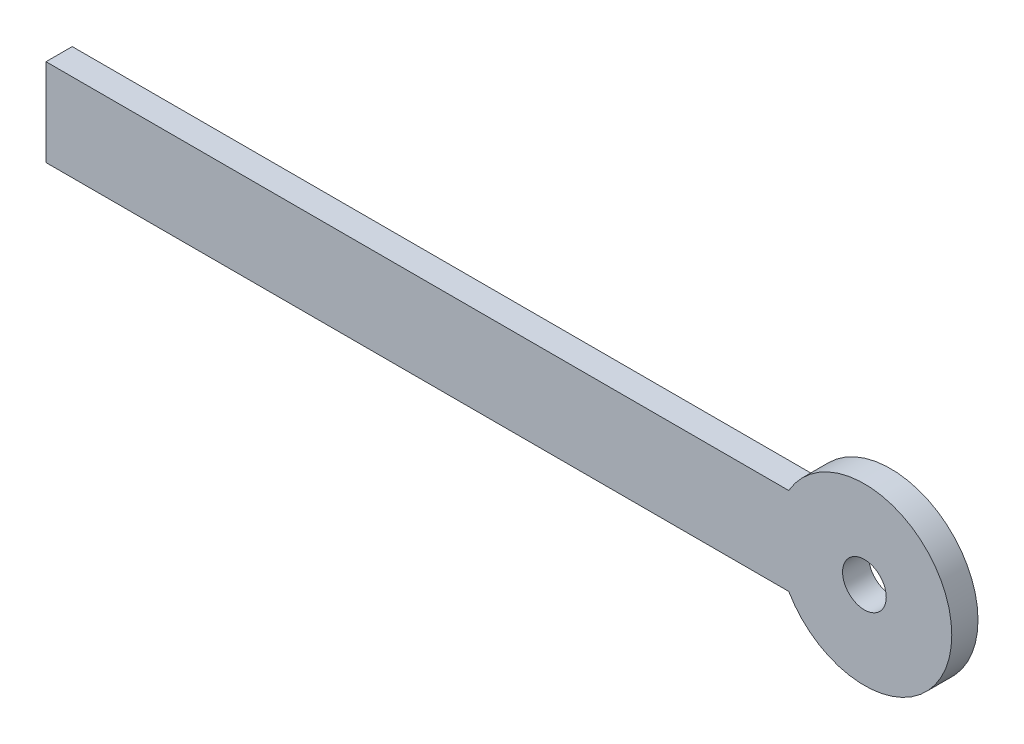
SolidWorks part; units mm, degrees
ref_plane "Front Plane" through (0, 0, 0) normal (0, 0, 1) x (1, 0, 0)
ref_plane "Top Plane" through (0, 0, 0) normal (0, 1, 0) x (1, 0, 0)
ref_plane "Right Plane" through (0, 0, 0) normal (1, 0, 0) x (0, 0, -1)
sketch "Sketch1" plane through (0, 0, 0) normal (0, 0, 1) x (1, 0, 0)
  line L0 (-93.6603, 5) -> (-8.6603, 5)
  line L1 (-93.6603, 5) -> (-93.6603, -5)
  line L2 (-93.6603, -5) -> (-8.6603, -5)
  line L3 (0, 0) -> (-66.4424, 0) construction
  arc A0 (-8.6603, -5) -> (-8.6603, 5) centre (0, 0) ccw
  circle A1 centre (0, 0) radius 2.5
  dimension "D1" = 20
  dimension "D2" = 5
  dimension "D3" = 5
  dimension "D4" = 5
  dimension "D5" = 85
extrude "Boss-Extrude1" add sketch "Sketch1" along normal blind 3
sketch "Sketch2" plane through (0, 0, 0) normal (0, 0, -1) x (-1, 0, 0)
  line L0 (0, 0) -> (0, 13.1896) construction
  line L1 (0, 0) -> (17.4591, 0) construction
  circle A1 centre (25, 0) radius 1.5
  dimension "D1" = 3
  dimension "D2" = 25
extrude "Cut-Extrude1" [suppressed] cut sketch "Sketch2" against normal blind 10
sketch "Sketch3" plane through (0, 0, 0) normal (0, 0, -1) x (-1, 0, 0)
  arc A3 (8.6603, 5) -> (8.6603, -5) centre (0, 0) ccw construction
  arc A4 (8.6603, 5) -> (8.6603, -5) centre (0, 0) ccw
extrude "Cut-Extrude2" [suppressed] cut sketch "Sketch3" against normal blind 10
